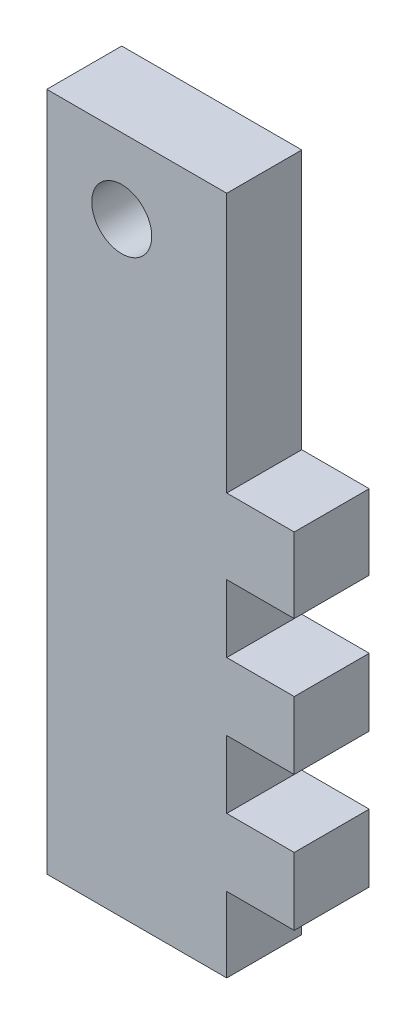
SolidWorks part; units mm, degrees
ref_plane "Plan de face" through (0, 0, 0) normal (0, 0, 1) x (1, 0, 0)
ref_plane "Plan de dessus" through (0, 0, 0) normal (0, 1, 0) x (1, 0, 0)
ref_plane "Plan de droite" through (0, 0, 0) normal (1, 0, 0) x (0, 0, -1)
sketch "Esquisse1" plane through (0, 0, 0) normal (0, 0, 1) x (1, 0, 0)
  line L0 (11.2978, 0.8457) -> (11.2978, 5.8457)
  line L1 (11.2978, 5.8457) -> (11.2978, 18.1551)
  line L2 (11.2978, 18.1551) -> (-0.7022, 18.1551)
  line L3 (-0.7022, 18.1551) -> (-0.7022, 5.8457)
  line L4 (-0.7022, 5.8457) -> (-0.7022, -27.1543)
  line L5 (-0.7022, -27.1543) -> (11.2978, -27.1543)
  line L6 (11.2978, -27.1543) -> (11.2978, -22.1543)
  line L7 (15.7978, -22.1543) -> (11.2978, -22.1543)
  line L8 (15.7978, -22.1543) -> (15.7978, -17.6543)
  line L9 (15.7978, -17.6543) -> (11.2978, -17.6543)
  line L10 (11.2978, -17.6543) -> (11.2978, -13.1543)
  line L11 (15.7978, -13.1543) -> (11.2978, -13.1543)
  line L12 (15.7978, -13.1543) -> (15.7978, -8.6543)
  line L13 (15.7978, -8.6543) -> (11.2978, -8.6543)
  line L14 (11.2978, -8.6543) -> (11.2978, -4.1543)
  line L15 (15.7978, -4.1543) -> (11.2978, -4.1543)
  line L16 (15.7978, -4.1543) -> (15.7978, 0.8457)
  line L17 (15.7978, 0.8457) -> (11.2978, 0.8457)
  circle A0 centre (4.2978, 13.1587) radius 2
extrude "Boss.-Extru.1" add sketch "Esquisse1" along normal blind 5
